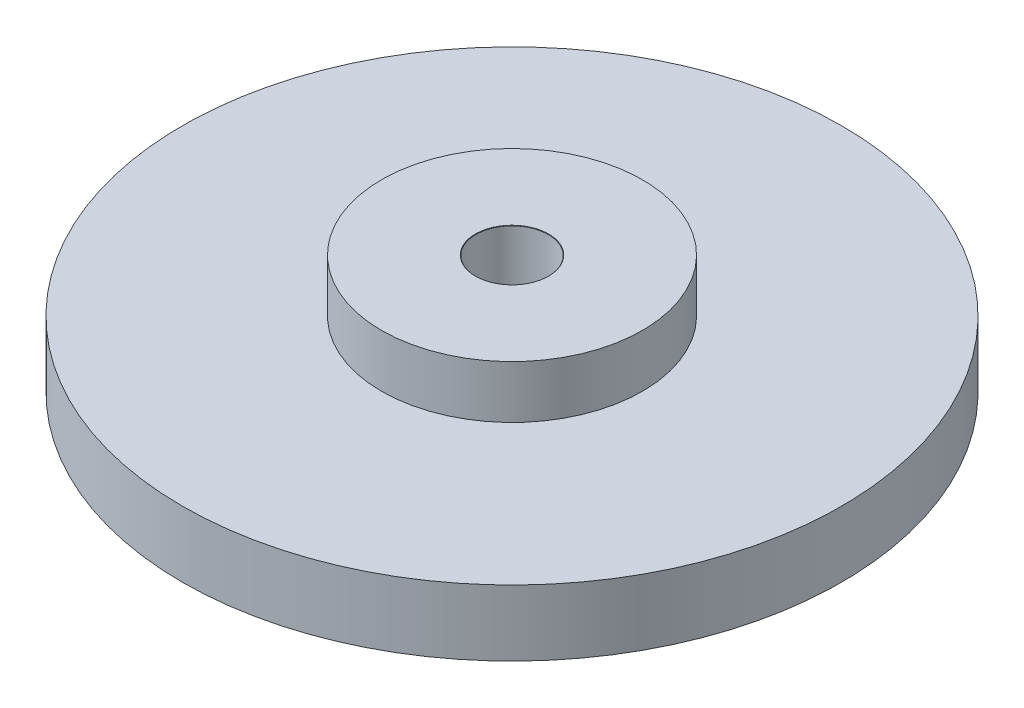
SolidWorks part; units mm, degrees
ref_plane "Front Plane" through (0, 0, 0) normal (0, 0, 1) x (1, 0, 0)
ref_plane "Top Plane" through (0, 0, 0) normal (0, 1, 0) x (1, 0, 0)
ref_plane "Right Plane" through (0, 0, 0) normal (1, 0, 0) x (0, 0, -1)
sketch "Sketch1" plane through (0, 0, 0) normal (0, 1, 0) x (1, 0, 0)
  circle A0 centre (0, 0) radius 25
  dimension "D1" = 50
extrude "Boss-Extrude1" add sketch "Sketch1" along normal blind 5
sketch "Sketch2" plane through (0, 5, 0) normal (0, 1, 0) x (1, 0, 0)
  circle A0 centre (0, 0) radius 9.9
  dimension "D1" = 19.8
extrude "Boss-Extrude2" add sketch "Sketch2" along normal blind 4
sketch "Sketch5" plane through (0, 9, 0) normal (0, 1, 0) x (1, 0, 0)
  point P0 (0, 0)
hole_wizard "M5 Clearance Hole1" positions "Sketch5" profile "Sketch4" hole size "M5" standard "ANSI Metric" end condition through all
sketch "Sketch4" plane through (0, 9, 0) normal (1, 0, 0) x (0, 0, 1)
  line L0 (0, 0) -> (0, 9)
  line L1 (0, 9) -> (2.75, 9)
  line L2 (2.75, 9) -> (2.75, 0.025)
  line L3 (2.75, 0.025) -> (2.775, 0)
  line L5 (2.775, 0) -> (0, 0)
  line L6 (-2.75, 0.025) -> (-2.775, 0) construction
  line L11 (0, -6.35) -> (0, 107.95) construction
  dimension "Thru Hole Dia." = 5.5
  dimension "Thru Hole Depth" = 9
  dimension "Near C'Sink Dia." = 5.55
  dimension "Near C'Sink Angle" = 90
